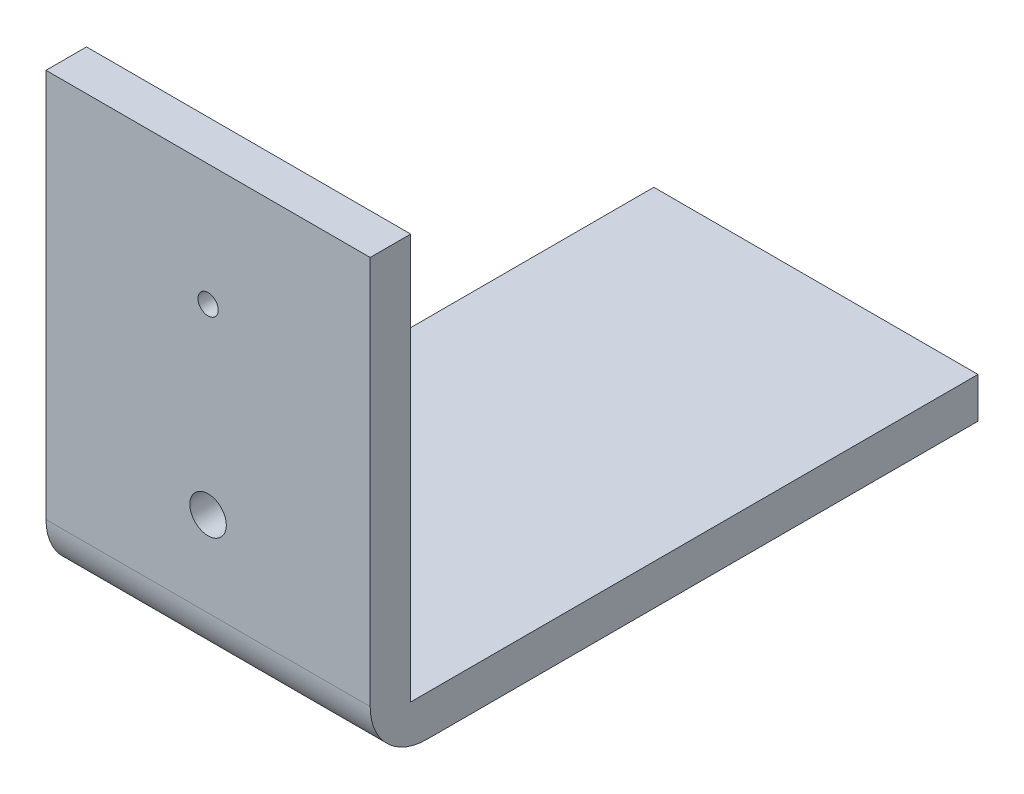
SolidWorks part; units mm, degrees
ref_plane "Alzado" through (0, 0, 0) normal (0, 0, 1) x (1, 0, 0)
ref_plane "Planta" through (0, 0, 0) normal (0, 1, 0) x (1, 0, 0)
ref_plane "Vista lateral" through (0, 0, 0) normal (1, 0, 0) x (0, 0, -1)
sketch "Croquis1" plane through (0, 0, 0) normal (0, 0, 1) x (1, 0, 0)
  line L1 (-15.5609, 15.8473) -> (24.4391, 15.8473)
  line L2 (-15.5609, 15.8473) -> (-15.5609, -34.1527)
  line L3 (-15.5609, -34.1527) -> (24.4391, -34.1527)
  line L4 (24.4391, 15.8473) -> (24.4391, -34.1527)
  dimension "D1" = 40
  dimension "D2" = 50
extrude "Saliente-Extruir1" add sketch "Croquis1" along normal blind 5
sketch "Croquis2" plane through (0, 0, 5) normal (0, 0, 1) x (1, 0, 0)
  line L0 (4.4391, 15.8473) -> (4.4391, -34.1527) construction
  line L1 (24.4391, 15.8473) -> (-15.5609, 15.8473) construction
  line L2 (-15.5609, -34.1527) -> (24.4391, -34.1527) construction
  circle A0 centre (4.4391, 0.8473) radius 1.25
  circle A1 centre (4.4391, -21.6527) radius 2.25
  dimension "D2" = 2.5
  dimension "D3" = 4.5
  dimension "D1" = 15
  dimension "D4" = 12.5
extrude "Cortar-Extruir2" cut sketch "Croquis2" against normal blind 5
sketch "Croquis4" plane through (0, -34.1527, 0) normal (0, -1, 0) x (1, 0, 0)
  line L1 (-15.5609, 5) -> (24.4391, 5)
  line L2 (-15.5609, 5) -> (-15.5609, -70)
  line L3 (-15.5609, -70) -> (24.4391, -70)
  line L4 (24.4391, 5) -> (24.4391, -70)
  dimension "D1" = 40
  dimension "D2" = 75
extrude "Saliente-Extruir2" add sketch "Croquis4" along normal blind 5
fillet "Redondeo1" radius 7 1 edges at (4.4391, -39.1527, 5)
